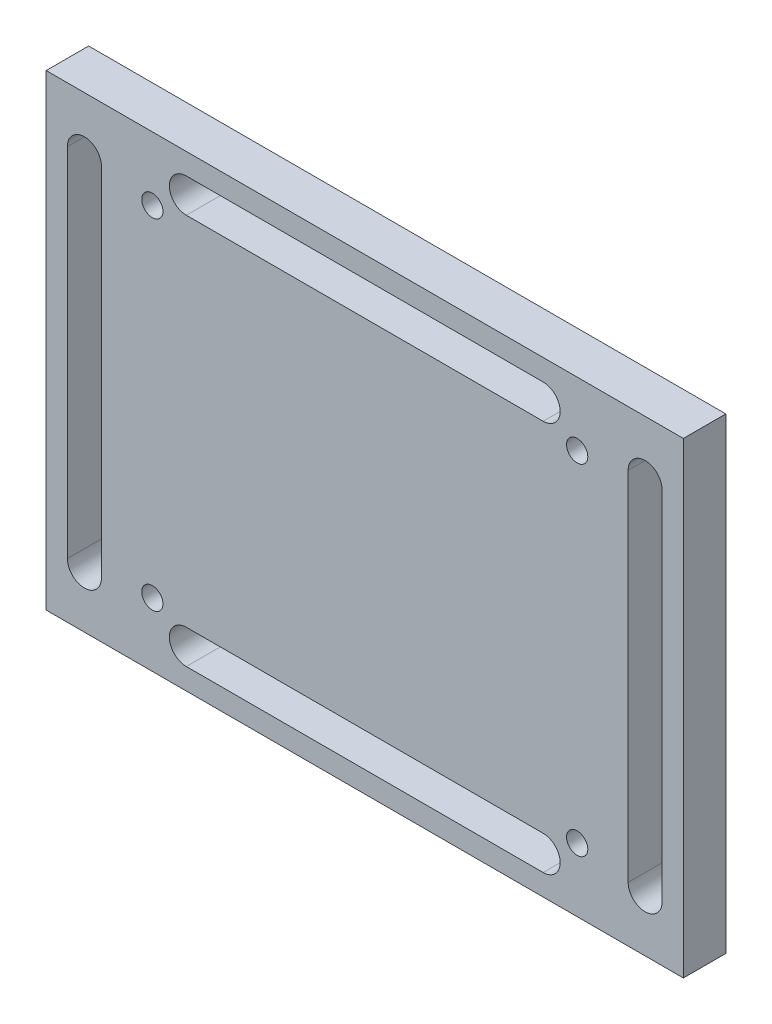
SolidWorks part; units mm, degrees
ref_plane "Front Plane" through (0, 0, 0) normal (0, 0, 1) x (1, 0, 0)
ref_plane "Top Plane" through (0, 0, 0) normal (0, 1, 0) x (1, 0, 0)
ref_plane "Right Plane" through (0, 0, 0) normal (1, 0, 0) x (0, 0, -1)
sketch "Sketch1" plane through (0, 0, 0) normal (0, 0, 1) x (1, 0, 0)
  line L0 (-21, 23) -> (21, 23) construction
  line L1 (-21, 25) -> (21, 25)
  line L2 (-21, 21) -> (21, 21)
  line L3 (-1000, 0) -> (49000, 0) construction
  line L4 (-37.5, 27.5) -> (-37.5, -27.5)
  line L5 (-37.5, -27.5) -> (37.5, -27.5)
  line L6 (37.5, -27.5) -> (37.5, 27.5)
  line L7 (37.5, 27.5) -> (-37.5, 27.5)
  line L8 (-37.5, 27.5) -> (-37.5, -27.5)
  line L9 (-37.5, -27.5) -> (37.5, -27.5)
  line L10 (37.5, -27.5) -> (37.5, 27.5)
  line L11 (37.5, 27.5) -> (-37.5, 27.5)
  line L12 (-21, -23) -> (21, -23) construction
  line L13 (-21, -25) -> (21, -25)
  line L14 (-21, -21) -> (21, -21)
  line L15 (0, -1000) -> (0, 49000) construction
  line L16 (-33, 21) -> (-33, -21) construction
  line L17 (-31, 21) -> (-31, -21)
  line L18 (-35, 21) -> (-35, -21)
  line L19 (33, 21) -> (33, -21) construction
  line L20 (31, 21) -> (31, -21)
  line L21 (35, 21) -> (35, -21)
  circle A0 centre (-25, 20) radius 1.25
  circle A1 centre (25, 20) radius 1.25
  circle A2 centre (25, -20) radius 1.25
  circle A3 centre (-25, -20) radius 1.25
  arc A4 (-21, 25) -> (-21, 21) centre (-21, 23) ccw
  arc A5 (21, 21) -> (21, 25) centre (21, 23) ccw
  arc A6 (-21, -25) -> (-21, -21) centre (-21, -23) cw
  arc A7 (21, -21) -> (21, -25) centre (21, -23) cw
  arc A8 (-31, 21) -> (-35, 21) centre (-33, 21) ccw
  arc A9 (-35, -21) -> (-31, -21) centre (-33, -21) ccw
  arc A10 (31, 21) -> (35, 21) centre (33, 21) cw
  arc A11 (35, -21) -> (31, -21) centre (33, -21) cw
  point P18 (0, 23)
  point P29 (0, -23)
  point P38 (-33, 0)
  point P47 (33, 0)
  dimension "D2" = 2.5
  dimension "D3" = 42
  dimension "D4" = 4
  dimension "D5" = 4.5
  dimension "D7" = 42
  dimension "D8" = 4
  dimension "D9" = 4.5
  dimension "D1" = 0
extrude "Boss-Extrude1" add sketch "Sketch1" along normal blind 5
